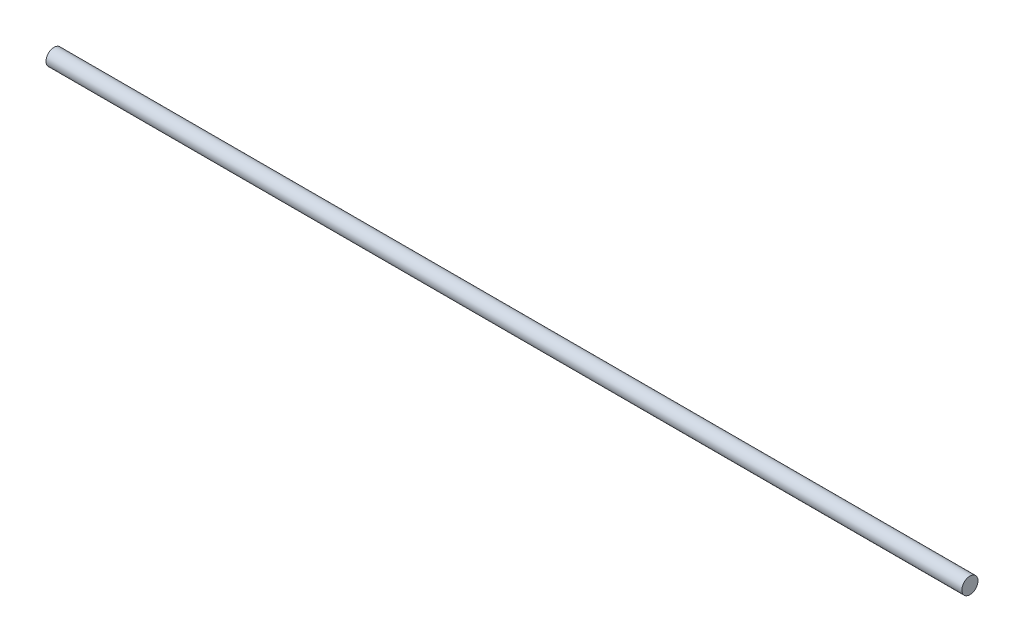
SolidWorks part; units mm, degrees
ref_plane "Front Plane" through (0, 0, 0) normal (0, 0, 1) x (1, 0, 0)
ref_plane "Top Plane" through (0, 0, 0) normal (0, 1, 0) x (1, 0, 0)
ref_plane "Right Plane" through (0, 0, 0) normal (1, 0, 0) x (0, 0, -1)
sketch "Sketch1" plane through (0, 0, 0) normal (1, 0, 0) x (0, 0, -1)
  circle A0 centre (0, 0) radius 3
  dimension "D1" = 6
extrude "Boss-Extrude1" add sketch "Sketch1" along normal mid plane 340
